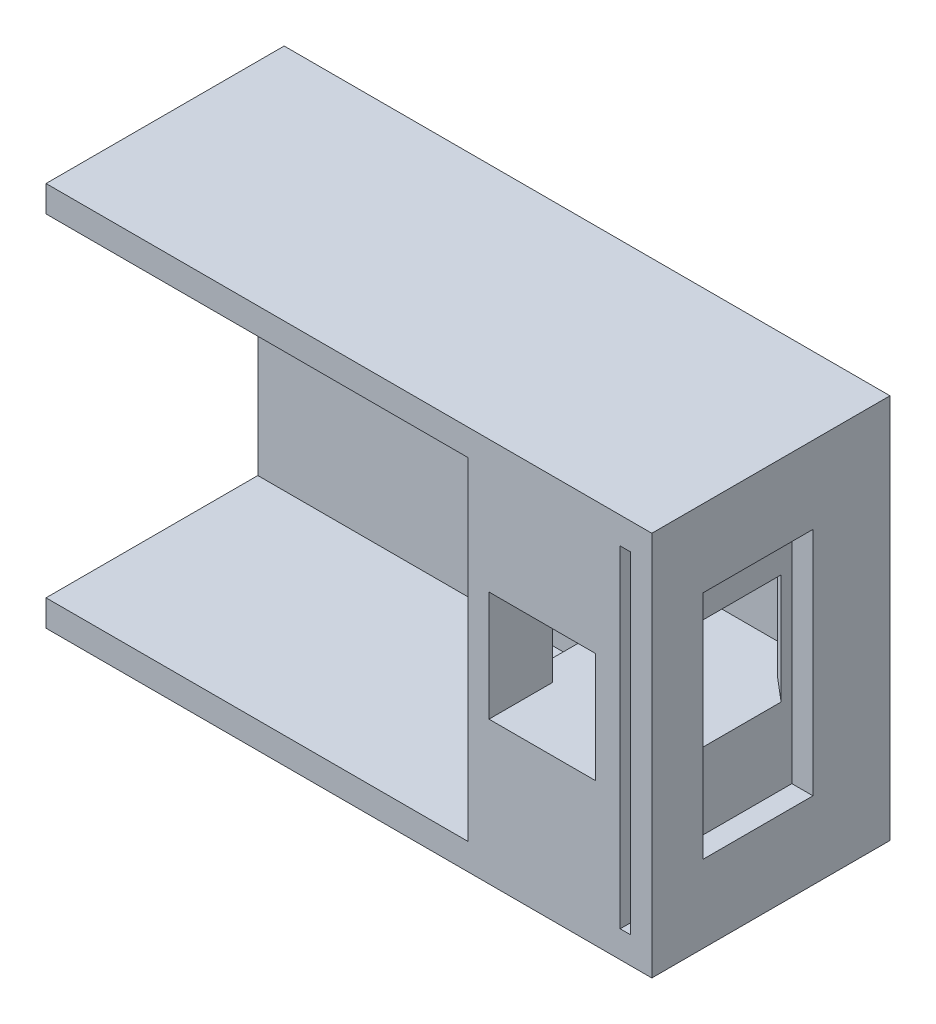
SolidWorks part; units mm, degrees
ref_plane "Alzado" through (0, 0, 0) normal (0, 0, 1) x (1, 0, 0)
ref_plane "Planta" through (0, 0, 0) normal (0, 1, 0) x (1, 0, 0)
ref_plane "Vista lateral" through (0, 0, 0) normal (1, 0, 0) x (0, 0, -1)
ref_plane "Plano1" through (0, 23.1902, 0) normal (0, 1, 0) x (1, 0, 0)
sketch "Croquis1" plane through (0, 23.1902, 0) normal (0, 1, 0) x (1, 0, 0)
  line L0 (50.8, -12.7508) -> (101.6, -12.7508)
  line L1 (101.6, -12.7508) -> (101.6, 12.7508)
  line L2 (101.6, 12.7508) -> (50.8, 12.7508)
  line L3 (50.8, 12.7508) -> (50.8, -12.7508)
extrude "Saliente-Extruir1" add sketch "Croquis1" against normal blind 3.175
sketch "Croquis2" plane through (101.6, 0, 0) normal (1, 0, 0) x (0, 0, -1)
  line L0 (-12.7508, -23.1902) -> (-12.7508, 23.1902)
  line L1 (-12.7508, 23.1902) -> (12.7508, 23.1902)
  line L2 (12.7508, 23.1902) -> (12.7508, -23.1902)
  line L3 (12.7508, -23.1902) -> (-12.7508, -23.1902)
extrude "Saliente-Extruir2" add sketch "Croquis2" along normal blind 18.3388
ref_plane "Plano2" through (0, -13.8938, 0) normal (0, -1, 0) x (1, 0, 0)
sketch "Croquis3" plane through (0, -13.8938, 0) normal (0, -1, 0) x (1, 0, 0)
  line L0 (101.6, -2.54) -> (104.14, -5.08)
  line L1 (104.14, -5.08) -> (104.14, -12.7508)
  line L2 (104.14, -12.7508) -> (117.3988, -12.7508)
  line L3 (117.3988, -12.7508) -> (117.3988, -9.1694)
  line L4 (117.3988, -9.1694) -> (119.9388, -6.6294)
  line L5 (119.9388, -6.6294) -> (119.9388, 6.6294)
  line L6 (119.9388, 6.6294) -> (117.3988, 9.1694)
  line L7 (117.3988, 9.1694) -> (117.3988, 12.7508)
  line L8 (117.3988, 12.7508) -> (104.14, 12.7508)
  line L9 (104.14, 12.7508) -> (104.14, 5.08)
  line L10 (104.14, 5.08) -> (101.6, 2.54)
  line L11 (101.6, 2.54) -> (101.6, -2.54)
ref_plane "Plano3" through (0, 7.26, 0) normal (0, 1, 0) x (1, 0, 0)
sketch "Croquis4" plane through (0, 7.26, 0) normal (0, 1, 0) x (1, 0, 0)
  line L0 (104.14, -5.08) -> (104.14, -12.7508)
  line L1 (104.14, -12.7508) -> (116.94, -12.7508)
  line L2 (116.94, -12.7508) -> (116.94, -9.1694)
  line L3 (116.94, -9.1694) -> (119.9388, -6.6294)
  line L4 (119.9388, -6.6294) -> (119.9388, 6.6294)
  line L5 (119.9388, 6.6294) -> (116.94, 9.1694)
  line L6 (116.94, 9.1694) -> (116.94, 12.7508)
  line L7 (116.94, 12.7508) -> (104.14, 12.7508)
  line L8 (104.14, 12.7508) -> (104.14, 5.08)
  line L9 (104.14, 5.08) -> (101.6, 2.54)
  line L10 (101.6, 2.54) -> (101.6, -2.54)
  line L11 (101.6, -2.54) -> (104.14, -5.08)
  dimension "D1" = 12.8
  dimension "D2" = 18.3388
extrude "Cortar-Extruir2" cut sketch "Croquis4" against normal blind 13.26
sketch "Croquis5" plane through (119.9388, 0, 0) normal (1, 0, 0) x (0, 0, -1)
  line L0 (-12.7508, -23.1902) -> (-12.7508, -19.9644)
  line L1 (-12.7508, -19.9644) -> (12.7, -19.9644)
  line L2 (12.7, -19.9644) -> (12.7, 19.9644)
  line L3 (12.7, 19.9644) -> (-12.7508, 19.9644)
  line L4 (-12.7508, 19.9644) -> (-12.7508, 23.1902)
  line L5 (-12.7508, 23.1902) -> (12.7508, 23.1902)
  line L6 (12.7508, 23.1902) -> (12.7508, -23.1902)
  line L7 (12.7508, -23.1902) -> (-12.7508, -23.1902)
extrude "Saliente-Extruir3" add sketch "Croquis5" along normal blind 1.27
sketch "Croquis6" plane through (121.2088, 0, 0) normal (1, 0, 0) x (0, 0, -1)
  line L0 (12.7508, -23.1902) -> (-12.7508, -23.1902)
  line L1 (-12.7508, -23.1902) -> (-12.7508, 23.1902)
  line L2 (-12.7508, 23.1902) -> (12.7508, 23.1902)
  line L3 (12.7508, 23.1902) -> (12.7508, -23.1902)
  line L4 (6.6514, 1.27) -> (6.6514, 13.8938)
  line L5 (6.6514, 13.8938) -> (-6.6074, 13.8938)
  line L6 (-6.6074, 13.8938) -> (-6.6074, -13.8938)
  line L7 (-6.6074, -13.8938) -> (6.6514, -13.8938)
  line L8 (6.6514, -13.8938) -> (6.6514, 1.27)
  point P10 (0, 0)
  point P11 (0, 0)
  point P12 (0, 0)
  point P13 (14.9125, 1.27)
  point P14 (0, 0)
  point P15 (6.615, 1.0534)
  dimension "D1" = 13.2588
extrude "Saliente-Extruir4" add sketch "Croquis6" along normal blind 2.54
sketch "Croquis7" plane through (101.6, 0, 0) normal (-1, 0, 0) x (0, 0, 1)
  line L0 (-12.7508, -20.0152) -> (12.7508, -20.0152)
  line L1 (12.7508, -20.0152) -> (12.7508, -23.1902)
  line L2 (12.7508, -23.1902) -> (-12.7508, -23.1902)
  line L3 (-12.7508, -23.1902) -> (-12.7508, -20.0152)
extrude "Saliente-Extruir5" add sketch "Croquis7" along normal blind 50.8
sketch "Croquis8" plane through (0, 0, -12.7508) normal (0, 0, -1) x (-1, 0, 0)
  line L0 (-50.8, 23.1902) -> (-50.8, -23.1902)
  line L1 (-50.8, -23.1902) -> (-123.7488, -23.1902)
  line L2 (-123.7488, -23.1902) -> (-123.7488, 23.1902)
  line L3 (-123.7488, 23.1902) -> (-50.8, 23.1902)
extrude "Saliente-Extruir6" add sketch "Croquis8" along normal blind 3.175
